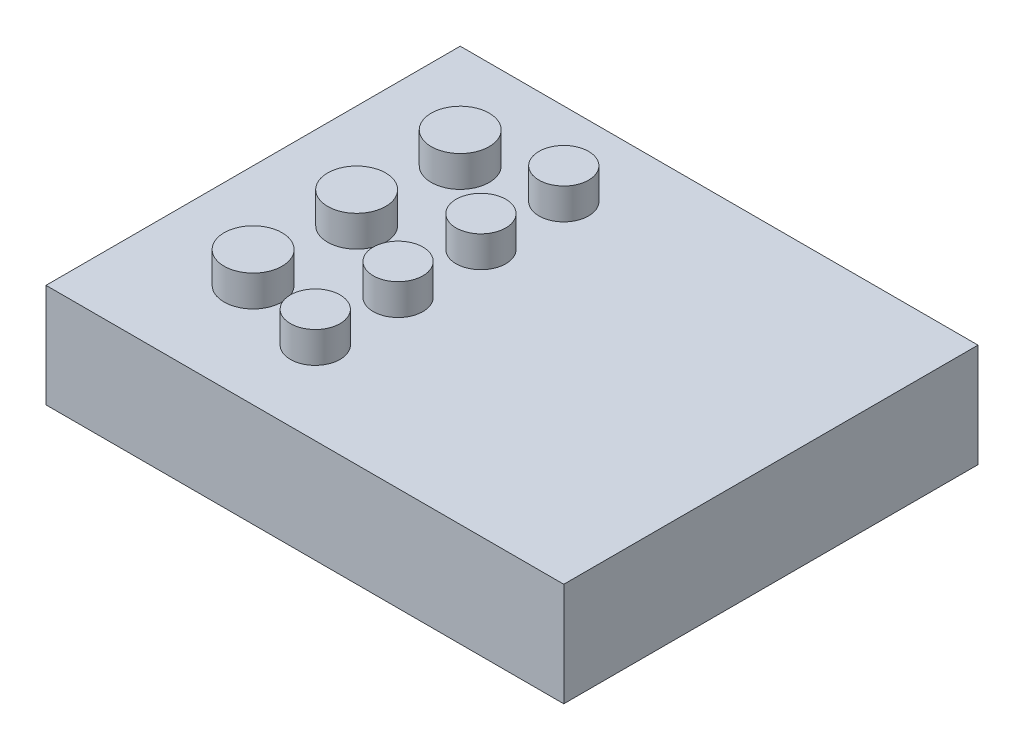
SolidWorks part; units mm, degrees
ref_plane "Front Plane" through (0, 0, 0) normal (0, 0, 1) x (1, 0, 0)
ref_plane "Top Plane" through (0, 0, 0) normal (0, 1, 0) x (1, 0, 0)
ref_plane "Right Plane" through (0, 0, 0) normal (1, 0, 0) x (0, 0, -1)
sketch "Sketch2" plane through (0, 0, 0) normal (0, 1, 0) x (1, 0, 0)
  line L1 (0, 0) -> (31.75, 0)
  line L2 (0, 0) -> (0, 25.4)
  line L3 (0, 25.4) -> (31.75, 25.4)
  line L4 (31.75, 0) -> (31.75, 25.4)
extrude "Boss-Extrude1" add sketch "Sketch2" along normal blind 6.35
sketch "Sketch4" plane through (0, 6.35, 0) normal (0, 1, 0) x (1, 0, 0)
  line L0 (0, 25.4) -> (6.35, 25.4)
  line L1 (31.75, 25.4) -> (0, 25.4) construction
  line L2 (6.35, 25.4) -> (11.43, 25.4)
  circle A0 centre (6.35, 19.05) radius 1.778
  circle A1 centre (6.35, 12.7) radius 1.778
  circle A2 centre (6.35, 6.35) radius 1.778
  circle A3 centre (11.43, 20.32) radius 1.524
  circle A4 centre (11.43, 15.24) radius 1.524
  circle A5 centre (11.43, 10.16) radius 1.524
  circle A6 centre (11.43, 5.08) radius 1.524
extrude "Boss-Extrude2" add sketch "Sketch4" along normal blind 1.905 contours A2 | A1 | A0 | A3 | A4 | A5 | A6
